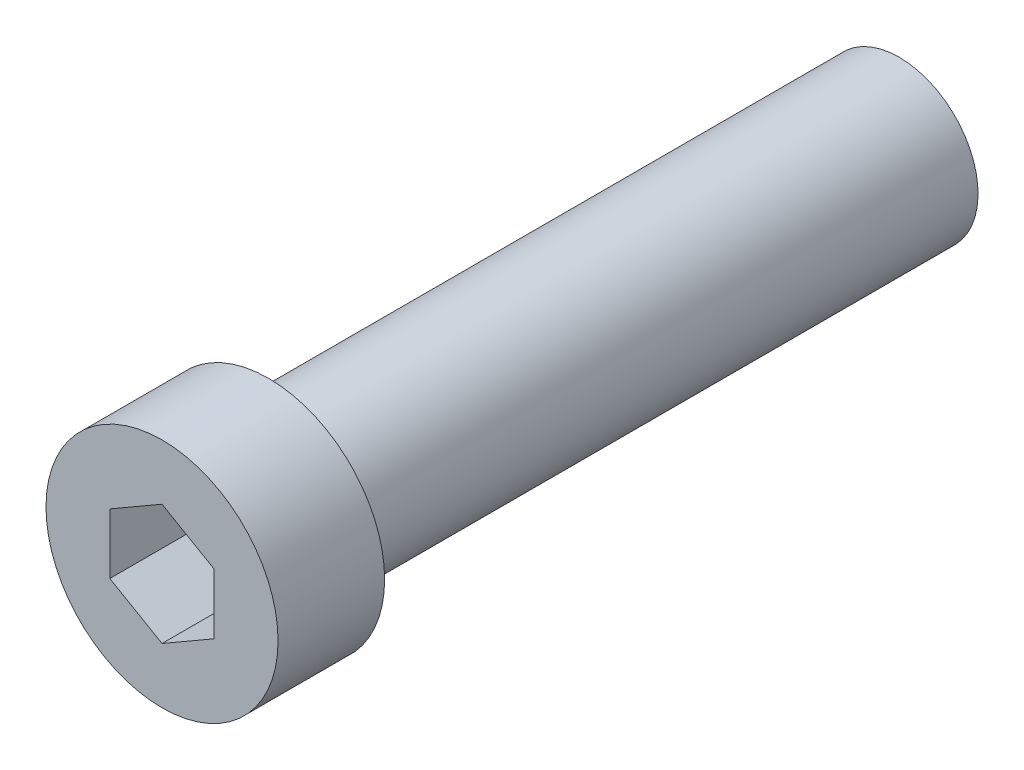
SolidWorks part; units mm, degrees
ref_plane "前视基准面" through (0, 0, 0) normal (0, 0, 1) x (1, 0, 0)
ref_plane "上视基准面" through (0, 0, 0) normal (0, 1, 0) x (1, 0, 0)
ref_plane "右视基准面" through (0, 0, 0) normal (1, 0, 0) x (0, 0, -1)
ref_plane "基准面1" through (0, 0, 0) normal (0, -1, 0) x (1, 0, 0)
sketch "草图1" plane through (0, 0, 0) normal (0, -1, 0) x (1, 0, 0)
  line L0 (2.208, 2.028) -> (0, 2.028)
  line L1 (0, 2.028) -> (0, 0)
  line L2 (0, 0) -> (2.208, 0)
  line L3 (2.208, 0) -> (2.208, 2.028)
  line L4 (0, 2.028) -> (0, 0) construction
revolve "旋转1" add sketch "草图1" angle 360 about L4
sketch "草图2" plane through (0, 0, 0) normal (0, 0, -1) x (-1, 0, 0)
  circle A0 centre (0, 0) radius 1.5
extrude "凸台-拉伸1" add sketch "草图2" along normal blind 12
sketch "草图3" plane through (0, 0, 2.028) normal (0, 0, 1) x (1, 0, 0)
  line L0 (0.9936, -0.5737) -> (0.9936, 0.5737)
  line L1 (0.9936, 0.5737) -> (0, 1.1473)
  line L2 (0, 1.1473) -> (-0.9936, 0.5737)
  line L3 (-0.9936, 0.5737) -> (-0.9936, -0.5737)
  line L4 (-0.9936, -0.5737) -> (0, -1.1473)
  line L5 (0, -1.1473) -> (0.9936, -0.5737)
extrude "切除-拉伸1" cut sketch "草图3" against normal blind 1.872
